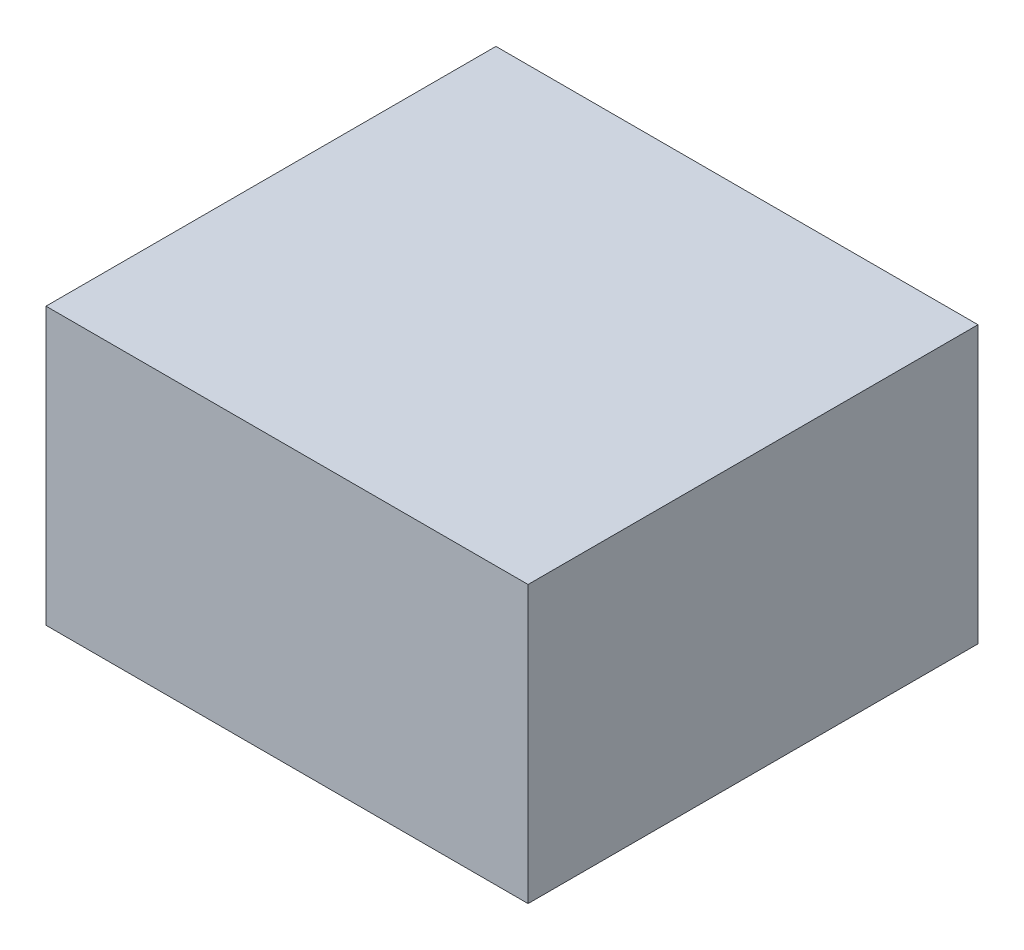
SolidWorks part; units mm, degrees
ref_plane "Спереди" through (0, 0, 0) normal (0, 0, 1) x (1, 0, 0)
ref_plane "Сверху" through (0, 0, 0) normal (0, 1, 0) x (1, 0, 0)
ref_plane "Справа" through (0, 0, 0) normal (1, 0, 0) x (0, 0, -1)
sketch "Эскиз1" plane through (0, 0, 0) normal (0, 0, 1) x (1, 0, 0)
  line L1 (0, 0) -> (150, 0)
  line L2 (0, 0) -> (0, 86)
  line L3 (0, 86) -> (150, 86)
  line L4 (150, 0) -> (150, 86)
  dimension "D1" = 150
  dimension "D2" = 86
extrude "Бобышка-Вытянуть1" add sketch "Эскиз1" along normal blind 140
